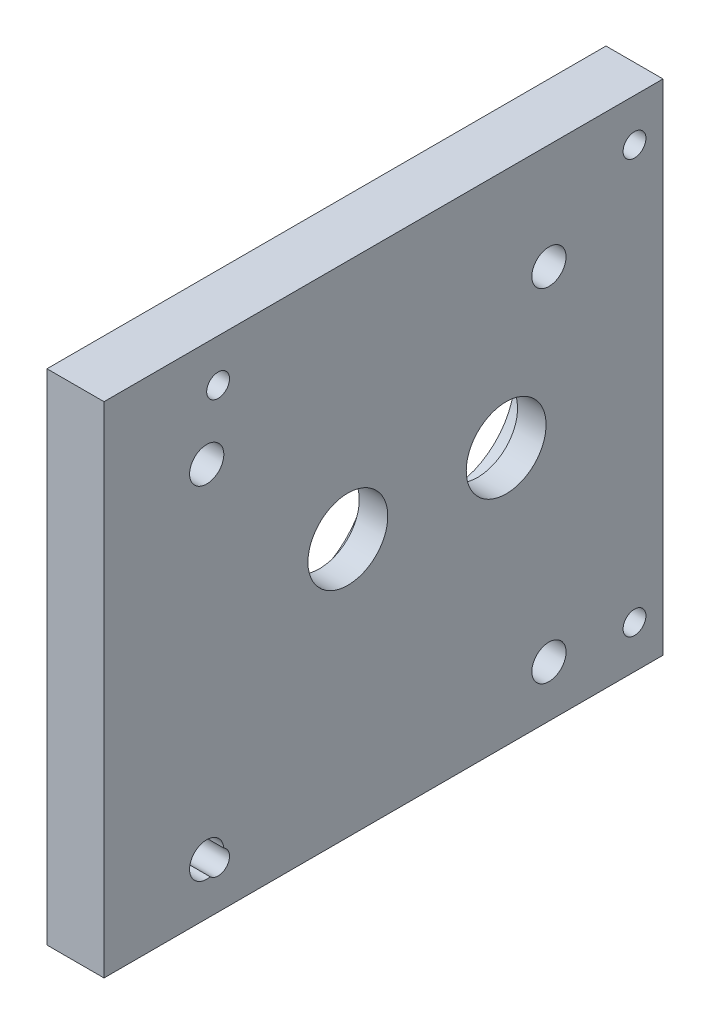
SolidWorks part; units mm, degrees
material "201 Annealed Stainless Steel (SS)"
ref_plane "Front Plane" through (0, 0, 0) normal (0, 0, 1) x (1, 0, 0)
ref_plane "Top Plane" through (0, 0, 0) normal (0, 1, 0) x (1, 0, 0)
ref_plane "Right Plane" through (0, 0, 0) normal (1, 0, 0) x (0, 0, -1)
sketch "Sketch1" plane through (114, 0, 0) normal (0, 1, 0) x (1, 0, 0)
  line L0 (-104, 0) -> (-114, 0) construction
  line L1 (-124, 98) -> (-104, 98)
  line L2 (-124, 98) -> (-124, -98)
  line L3 (-124, -98) -> (-104, -98)
  line L4 (-104, 98) -> (-104, -98)
  line L5 (-114, -96.25) -> (-114, 96.25) construction
  point P9 (-114, -98)
  dimension "D1" = 20
  dimension "D2" = 196
extrude "Boss-Extrude1" add sketch "Sketch1" along normal blind 175
sketch "Sketch2" plane through (-10, 0, 0) normal (-1, 0, 0) x (0, 0, 1)
  line L2 (0, -11) -> (0, 11) construction
  line L3 (0, -96.25) -> (0, 96.25) construction
  line L4 (98, 175) -> (98, 0) construction
  line L5 (-98, 0) -> (98, 0) construction
  line L6 (-98, 175) -> (-98, 0) construction
  circle A1 centre (12.5, 90.5) radius 27.5
  circle A2 centre (-43, 90.5) radius 23
  dimension "D1" = 55
  dimension "D2" = 46
  dimension "D5" = 58
  dimension "D6" = 63
  dimension "D7" = 90.5
  dimension "D8" = 32
  dimension "D3" = 12.5
  dimension "D4" = 43
extrude "Cut-Extrude1" cut sketch "Sketch2" against normal blind 10
sketch "Sketch3" plane through (0, 0, 0) normal (-1, 0, 0) x (0, 0, 1)
  circle A0 centre (12.5, 90.5) radius 14
  circle A1 centre (-43, 90.5) radius 14
  circle A2 centre (-43, 90.5) radius 23 construction
  circle A3 centre (12.5, 90.5) radius 27.5 construction
  dimension "D1" = 28
extrude "Cut-Extrude2" cut sketch "Sketch3" against normal through all
sketch "Sketch4" plane through (-10, 0, 0) normal (-1, 0, 0) x (0, 0, 1)
  circle A1 centre (58, 15) radius 4
  circle A2 centre (58, 15) radius 4
  circle A3 centre (-88, 15) radius 4
  circle A4 centre (-88, 15) radius 4
  circle A5 centre (-88, 160) radius 4
  circle A6 centre (-88, 160) radius 4
  circle A7 centre (58, 160) radius 4
  circle A8 centre (58, 160) radius 4
  dimension "D1" = 0
  dimension "D2" = 0
  dimension "D3" = 0
  dimension "D4" = 0
extrude "Cut-Extrude3" cut sketch "Sketch4" against normal through all
sketch "Sketch5" plane through (-10, 0, 0) normal (-1, 0, 0) x (0, 0, 1)
  line L0 (2, 149.9257) -> (2, 78) construction
  line L1 (2, 78) -> (116.2382, 78) construction
  line L2 (98, 175) -> (98, 0) construction
  line L3 (-98, 175) -> (98, 175) construction
  circle A0 centre (62, 138) radius 6
  circle A1 centre (62, 18) radius 6
  circle A2 centre (-58, 138) radius 6
  circle A3 centre (-58, 18) radius 6
  dimension "D1" = 12
  dimension "D2" = 132
  dimension "D3" = 132
  dimension "D4" = 30
  dimension "D5" = 31
extrude "Cut-Extrude4" cut sketch "Sketch5" against normal through all
ref_plane "Centre Bolts PLane  Vertical" through (0, 0, 2) normal (0, 0, 1) x (0, -1, 0)
ref_plane "Centre Bolts PLane Horizontal" through (0, 78, 0) normal (0, 1, 0) x (1, 0, 0)
sketch "Sketch6" plane through (0, 0, 0) normal (0, -1, 0) x (1, 0, 0)
  line L0 (0, -15) -> (-33.6897, -15) construction
  line L2 (256.8915, -15) -> (199.1085, -15) construction
  circle A0 centre (0, -65) radius 4
  circle A1 centre (0, 35) radius 4
  point P7 (0, 0)
  dimension "D1" = 8
  dimension "D2" = 100
extrude "Cut-Extrude6" cut sketch "Sketch6" against normal blind 12
